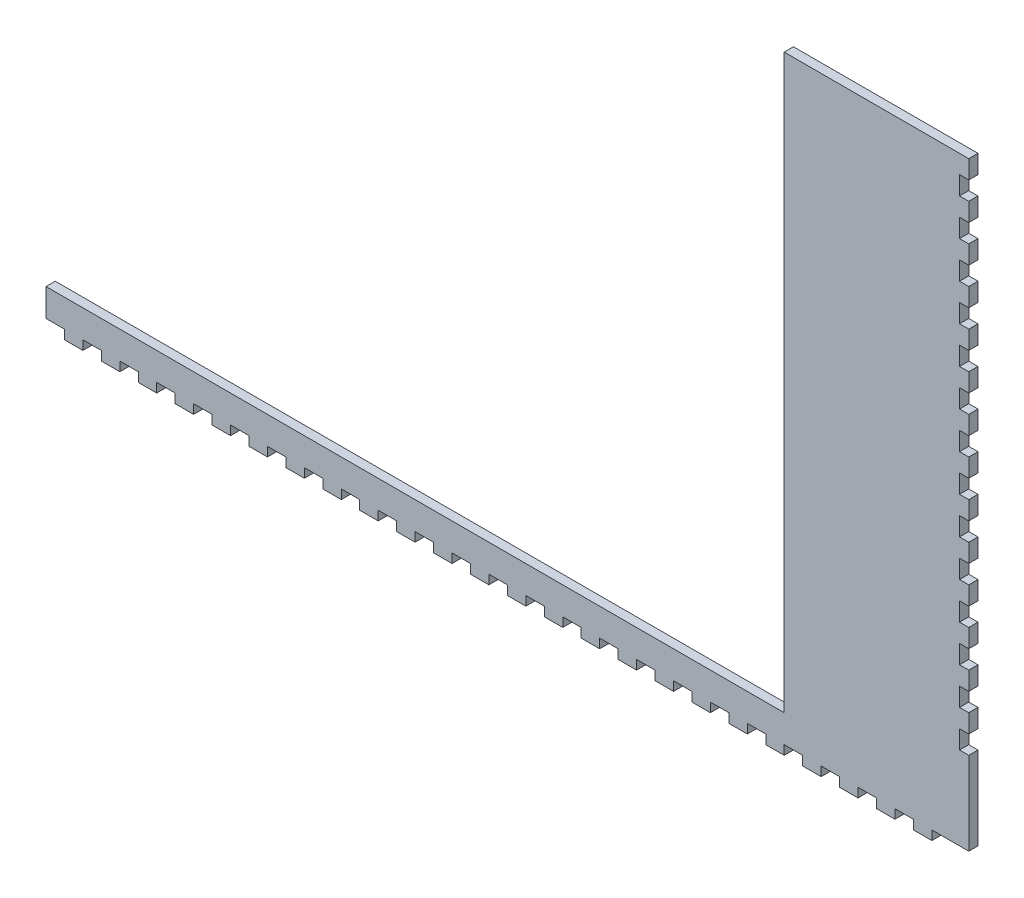
SolidWorks part; units mm, degrees
ref_plane "Plan de face" through (0, 0, 0) normal (0, 0, 1) x (1, 0, 0)
ref_plane "Plan de dessus" through (0, 0, 0) normal (0, 1, 0) x (1, 0, 0)
ref_plane "Plan de droite" through (0, 0, 0) normal (1, 0, 0) x (0, 0, -1)
sketch "Esquisse1" plane through (0, 0, 0) normal (0, 0, 1) x (1, 0, 0)
  line L0 (400, 20) -> (400, 330)
  line L1 (0, 0) -> (400, 0)
  line L2 (0, 0) -> (0, 20)
  line L3 (0, 20) -> (400, 20)
  line L9 (400, 330) -> (500, 330)
  line L10 (500, 330) -> (500, 0)
  line L11 (500, 0) -> (400, 0)
  dimension "D1" = 400
  dimension "D2" = 20
  dimension "D3" = 100
  dimension "D4" = 330
extrude "Boss.-Extru.1" add sketch "Esquisse1" along normal blind 5
sketch "Esquisse2" plane through (0, 0, 5) normal (0, 0, 1) x (1, 0, 0)
  line L0 (20, 0) -> (20, 5)
  line L1 (0, 0) -> (10, 0)
  line L2 (0, 0) -> (0, 5)
  line L3 (0, 5) -> (10, 5)
  line L4 (10, 0) -> (10, 5)
  line L5 (20, 0) -> (30, 0)
  line L6 (30, 0) -> (30, 5)
  line L7 (20, 5) -> (30, 5)
  line L8 (40, 0) -> (40, 5)
  line L9 (40, 0) -> (50, 0)
  line L10 (50, 0) -> (50, 5)
  line L11 (40, 5) -> (50, 5)
  line L12 (60, 0) -> (60, 5)
  line L13 (60, 0) -> (70, 0)
  line L14 (70, 0) -> (70, 5)
  line L15 (60, 5) -> (70, 5)
  line L16 (80, 0) -> (80, 5)
  line L17 (80, 0) -> (90, 0)
  line L18 (90, 0) -> (90, 5)
  line L19 (80, 5) -> (90, 5)
  line L20 (100, 0) -> (100, 5)
  line L21 (100, 0) -> (110, 0)
  line L22 (110, 0) -> (110, 5)
  line L23 (100, 5) -> (110, 5)
  line L24 (120, 0) -> (120, 5)
  line L25 (120, 0) -> (130, 0)
  line L26 (130, 0) -> (130, 5)
  line L27 (120, 5) -> (130, 5)
  line L28 (140, 0) -> (140, 5)
  line L29 (140, 0) -> (150, 0)
  line L30 (150, 0) -> (150, 5)
  line L31 (140, 5) -> (150, 5)
  line L32 (160, 0) -> (160, 5)
  line L33 (160, 0) -> (170, 0)
  line L34 (170, 0) -> (170, 5)
  line L35 (160, 5) -> (170, 5)
  line L36 (180, 0) -> (180, 5)
  line L37 (180, 0) -> (190, 0)
  line L38 (190, 0) -> (190, 5)
  line L39 (180, 5) -> (190, 5)
  line L40 (200, 0) -> (200, 5)
  line L41 (200, 0) -> (210, 0)
  line L42 (210, 0) -> (210, 5)
  line L43 (200, 5) -> (210, 5)
  line L44 (220, 0) -> (220, 5)
  line L45 (220, 0) -> (230, 0)
  line L46 (230, 0) -> (230, 5)
  line L47 (220, 5) -> (230, 5)
  line L48 (240, 0) -> (240, 5)
  line L49 (240, 0) -> (250, 0)
  line L50 (250, 0) -> (250, 5)
  line L51 (240, 5) -> (250, 5)
  line L52 (260, 0) -> (260, 5)
  line L53 (260, 0) -> (270, 0)
  line L54 (270, 0) -> (270, 5)
  line L55 (260, 5) -> (270, 5)
  line L56 (280, 0) -> (280, 5)
  line L57 (280, 0) -> (290, 0)
  line L58 (290, 0) -> (290, 5)
  line L59 (280, 5) -> (290, 5)
  line L60 (300, 0) -> (300, 5)
  line L61 (300, 0) -> (310, 0)
  line L62 (310, 0) -> (310, 5)
  line L63 (300, 5) -> (310, 5)
  line L64 (320, 0) -> (320, 5)
  line L65 (320, 0) -> (330, 0)
  line L66 (330, 0) -> (330, 5)
  line L67 (320, 5) -> (330, 5)
  line L68 (340, 0) -> (340, 5)
  line L69 (340, 0) -> (350, 0)
  line L70 (350, 0) -> (350, 5)
  line L71 (340, 5) -> (350, 5)
  line L72 (360, 0) -> (360, 5)
  line L73 (360, 0) -> (370, 0)
  line L74 (370, 0) -> (370, 5)
  line L75 (360, 5) -> (370, 5)
  line L76 (380, 0) -> (380, 5)
  line L77 (380, 0) -> (390, 0)
  line L78 (390, 0) -> (390, 5)
  line L79 (380, 5) -> (390, 5)
  line L80 (400, 0) -> (400, 5)
  line L81 (400, 0) -> (410, 0)
  line L82 (410, 0) -> (410, 5)
  line L83 (400, 5) -> (410, 5)
  line L84 (420, 0) -> (420, 5)
  line L85 (420, 0) -> (430, 0)
  line L86 (430, 0) -> (430, 5)
  line L87 (420, 5) -> (430, 5)
  line L88 (440, 0) -> (440, 5)
  line L89 (440, 0) -> (450, 0)
  line L90 (450, 0) -> (450, 5)
  line L91 (440, 5) -> (450, 5)
  line L92 (460, 0) -> (460, 5)
  line L93 (460, 0) -> (470, 0)
  line L94 (470, 0) -> (470, 5)
  line L95 (460, 5) -> (470, 5)
  line L96 (480, 0) -> (480, 5)
  line L97 (480, 0) -> (490, 0)
  line L99 (480, 5) -> (490, 5)
  line L102 (490, 5) -> (500, 5)
  line L103 (500, 0) -> (500, 5)
  line L104 (490, 0) -> (500, 0)
  line L105 (490, 0) -> (490, 5) [skipped]
  line L106 (490, 0) -> (490, 5) [skipped]
  line L107 (500, 0) -> (500, 330) construction
  line L108 (500, 320) -> (495, 320)
  line L109 (500, 320) -> (500, 310)
  line L110 (500, 310) -> (495, 310)
  line L111 (495, 320) -> (495, 310)
  line L112 (500, 330) -> (400, 330) construction
  line L113 (500, 300) -> (500, 290)
  line L114 (500, 300) -> (495, 300)
  line L115 (495, 300) -> (495, 290)
  line L116 (500, 290) -> (495, 290)
  line L117 (500, 280) -> (500, 270)
  line L118 (500, 280) -> (495, 280)
  line L119 (495, 280) -> (495, 270)
  line L120 (500, 270) -> (495, 270)
  line L121 (500, 260) -> (500, 250)
  line L122 (500, 260) -> (495, 260)
  line L123 (495, 260) -> (495, 250)
  line L124 (500, 250) -> (495, 250)
  line L125 (500, 240) -> (500, 230)
  line L126 (500, 240) -> (495, 240)
  line L127 (495, 240) -> (495, 230)
  line L128 (500, 230) -> (495, 230)
  line L129 (500, 220) -> (500, 210)
  line L130 (500, 220) -> (495, 220)
  line L131 (495, 220) -> (495, 210)
  line L132 (500, 210) -> (495, 210)
  line L133 (500, 200) -> (500, 190)
  line L134 (500, 200) -> (495, 200)
  line L135 (495, 200) -> (495, 190)
  line L136 (500, 190) -> (495, 190)
  line L137 (500, 180) -> (500, 170)
  line L138 (500, 180) -> (495, 180)
  line L139 (495, 180) -> (495, 170)
  line L140 (500, 170) -> (495, 170)
  line L141 (500, 160) -> (500, 150)
  line L142 (500, 160) -> (495, 160)
  line L143 (495, 160) -> (495, 150)
  line L144 (500, 150) -> (495, 150)
  line L145 (500, 140) -> (500, 130)
  line L146 (500, 140) -> (495, 140)
  line L147 (495, 140) -> (495, 130)
  line L148 (500, 130) -> (495, 130)
  line L149 (500, 120) -> (500, 110)
  line L150 (500, 120) -> (495, 120)
  line L151 (495, 120) -> (495, 110)
  line L152 (500, 110) -> (495, 110)
  line L153 (500, 100) -> (500, 90)
  line L154 (500, 100) -> (495, 100)
  line L155 (495, 100) -> (495, 90)
  line L156 (500, 90) -> (495, 90)
  line L157 (500, 80) -> (500, 70)
  line L158 (500, 80) -> (495, 80)
  line L159 (495, 80) -> (495, 70)
  line L160 (500, 70) -> (495, 70)
  line L161 (500, 60) -> (500, 50)
  line L162 (500, 60) -> (495, 60)
  line L163 (495, 60) -> (495, 50)
  line L164 (500, 50) -> (495, 50)
  dimension "D1" = 10
  dimension "D2" = 5
  dimension "D4" = 2
  dimension "D5" = 10
  dimension "D6" = 5
  dimension "D7" = 10
  dimension "D3" = 25
  dimension "D8" = 14
extrude "Enlèv. mat.-Extru.2" cut sketch "Esquisse2" against normal through all
